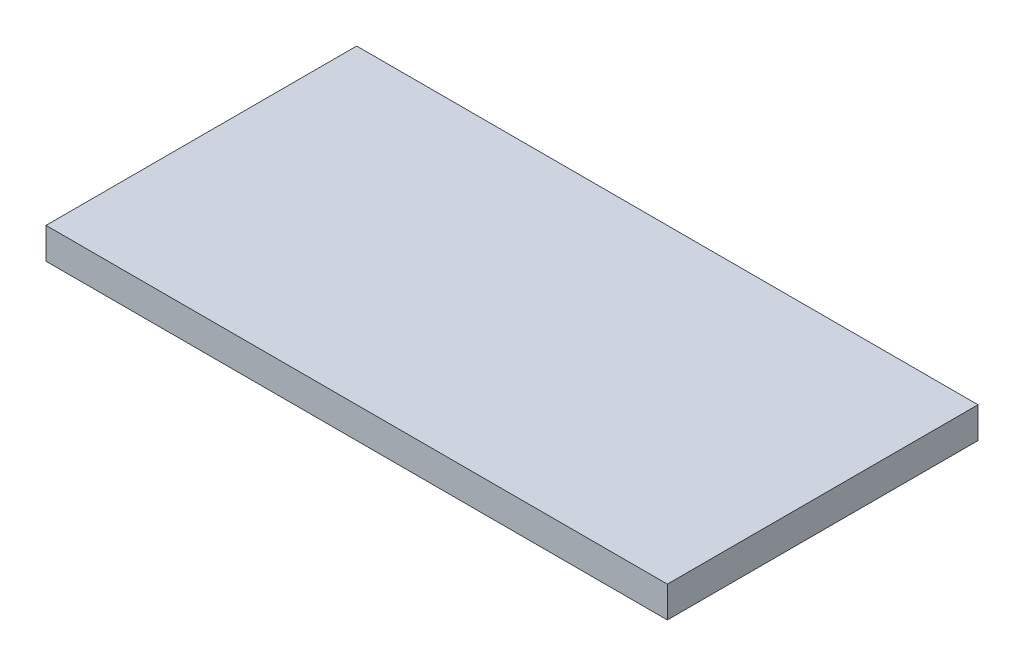
SolidWorks part; units mm, degrees
ref_plane "前视基准面" through (0, 0, 0) normal (0, 0, 1) x (1, 0, 0)
ref_plane "上视基准面" through (0, 0, 0) normal (0, 1, 0) x (1, 0, 0)
ref_plane "右视基准面" through (0, 0, 0) normal (1, 0, 0) x (0, 0, -1)
other "Configuration Table"
sketch "草图1" plane through (0, 0, 0) normal (0, 1, 0) x (1, 0, 0)
  line L1 (-1.8405, 0) -> (198.1595, 0)
  line L2 (-1.8405, 0) -> (-1.8405, -100)
  line L3 (-1.8405, -100) -> (198.1595, -100)
  line L4 (198.1595, 0) -> (198.1595, -100)
  dimension "D1" = 200
  dimension "D2" = 100
extrude "凸台-拉伸1" add sketch "草图1" along normal blind 10 contours L1 L4 L3 L2
